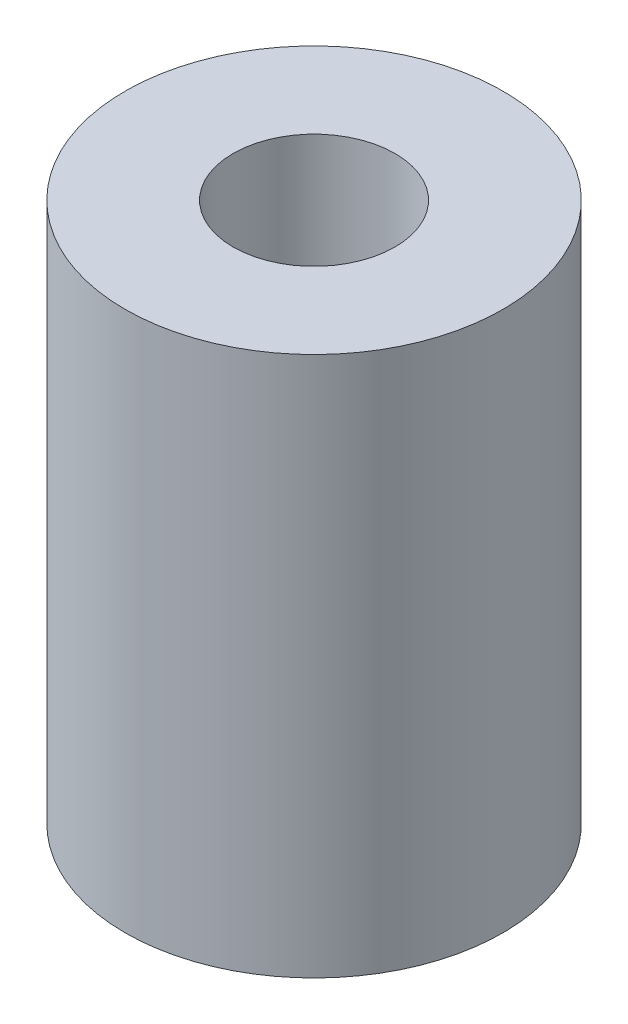
SolidWorks part; units mm, degrees
ref_plane "Front Plane" through (0, 0, 0) normal (0, 0, 1) x (1, 0, 0)
ref_plane "Top Plane" through (0, 0, 0) normal (0, 1, 0) x (1, 0, 0)
ref_plane "Right Plane" through (0, 0, 0) normal (1, 0, 0) x (0, 0, -1)
sketch "Sketch1" plane through (0, 0, 0) normal (0, 1, 0) x (1, 0, 0)
  circle A0 centre (0, 0) radius 3.5
  circle A1 centre (0, 0) radius 1.5
  dimension "D1" = 3
  dimension "D2" = 7
extrude "Boss-Extrude1" add sketch "Sketch1" along normal blind 10
